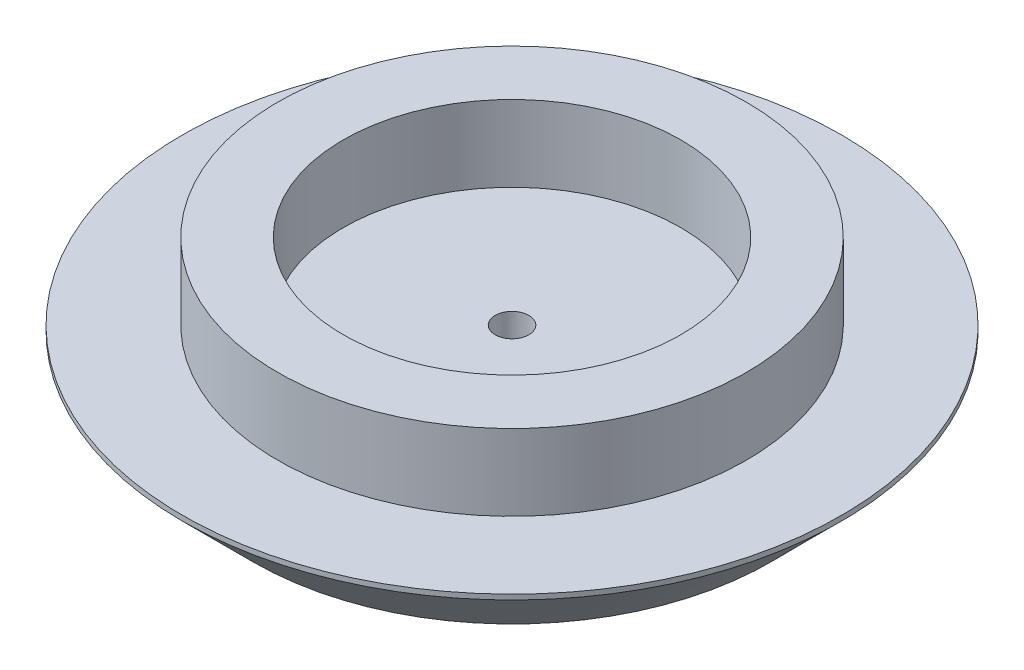
SolidWorks part; units mm, degrees
material "PE Low/Medium Density"
ref_plane "Front Plane" through (0, 0, 0) normal (0, 0, 1) x (1, 0, 0)
ref_plane "Top Plane" through (0, 0, 0) normal (0, 1, 0) x (1, 0, 0)
ref_plane "Right Plane" through (0, 0, 0) normal (1, 0, 0) x (0, 0, -1)
sketch "Sketch1" plane through (0, 0, 0) normal (0, 0, 1) x (1, 0, 0)
  line L0 (-29.337, 0) -> (-41.275, 0)
  line L1 (-29.337, 0) -> (-29.337, 9.525)
  line L2 (-29.337, 9.525) -> (-21.1455, 9.525)
  line L3 (-21.1455, 9.525) -> (-21.1455, 0)
  line L4 (-21.1455, 0) -> (0, 0)
  line L5 (-41.275, 0) -> (-41.275, -9.525)
  line L6 (-41.275, -9.525) -> (0, -9.525)
  line L7 (0, -9.525) -> (0, 0)
  dimension "D1" = 9.525
  dimension "D2" = 9.525
  dimension "D3" = 21.1455
  dimension "D4" = 29.337
  dimension "D5" = 41.275
revolve "Revolve1" add sketch "Sketch1" angle 360 about L7
chamfer "Chamfer1" distance 8.89 angle 45 1 edges at (0, -9.525, -41.275)
sketch "Sketch9" plane through (0, -9.525, 0) normal (0, -1, 0) x (1, 0, 0)
  line L0 (0, 0) -> (0, 32.385) construction
  circle A0 centre (0, 0) radius 32.385 construction
hole_wizard "#19 (0.166) Diameter Hole1" positions "3DSketch5" profile "Sketch11" hole size "#19" standard "Ansi Inch" end condition up to next
sketch3d "3DSketch5"
  point P0 (0, -9.525, 0)
sketch "Sketch11" plane through (0, -9.525, 0) normal (1, 0, 0) x (0, 0, -1)
  line L0 (0, 0) -> (0, 9.525)
  line L1 (0, 9.525) -> (2.1082, 9.525)
  line L2 (2.1082, 9.525) -> (2.1082, 0)
  line L5 (2.1082, 0) -> (0, 0)
  line L11 (0, -6.35) -> (0, 107.95) construction
  dimension "Thru Hole Dia." = 4.2164
  dimension "Thru Hole Depth" = 9.525
